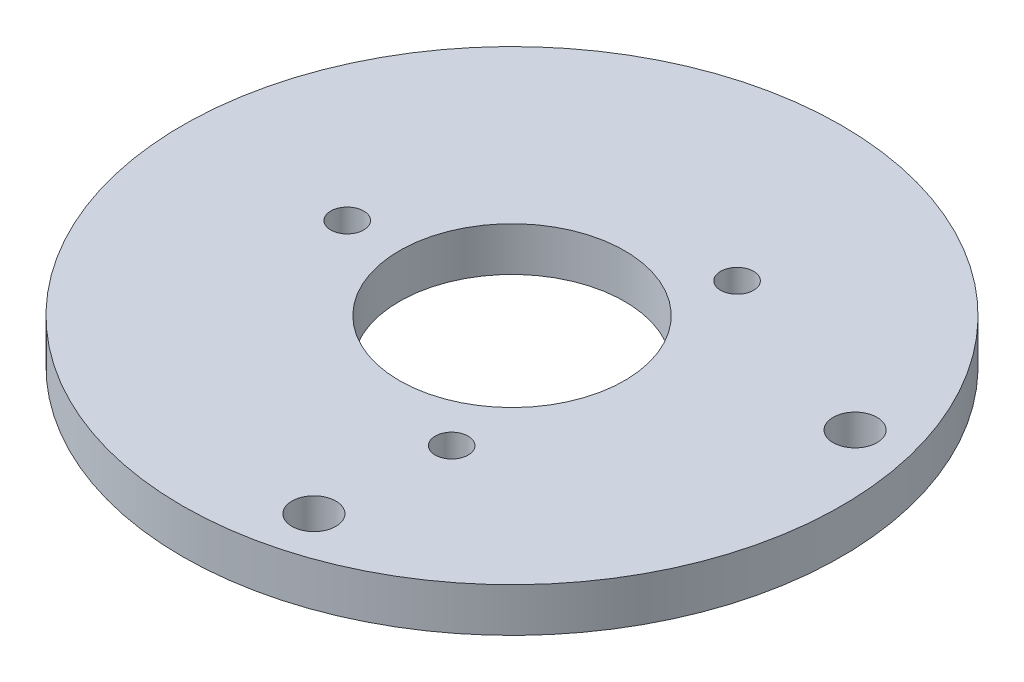
SolidWorks part; units mm, degrees
material "1060 Alloy"
ref_plane "Front Plane" through (0, 0, 0) normal (0, 0, 1) x (1, 0, 0)
ref_plane "Top Plane" through (0, 0, 0) normal (0, 1, 0) x (1, 0, 0)
ref_plane "Right Plane" through (0, 0, 0) normal (1, 0, 0) x (0, 0, -1)
sketch "Sketch1" plane through (0, 0, 0) normal (0, 1, 0) x (1, 0, 0)
  line L0 (-44.2539, 0) -> (44.2539, 0) construction
  arc A0 (-30, 0) -> (30, 0) centre (0, 0) cw
  arc A2 (-30, 0) -> (30, 0) centre (0, 0) ccw
  dimension "D1" = 30
extrude "Boss-Extrude1" add sketch "Sketch1" along normal blind 4
sketch "Sketch2" plane through (0, 4, 0) normal (0, 1, 0) x (1, 0, 0)
  line L2 (0, -44.7868) -> (0, 44.7868) construction
  circle A0 centre (7.5, 12.9904) radius 1.5
  dimension "D1" = 3
  dimension "D2" = 15
  dimension "D3" = 7.5
extrude "Cut-Extrude1" cut sketch "Sketch2" against normal blind 4
pattern_circular "CirPattern1" count 3 over 360 about axis through (0, 0, 0) along (0, 1, 0) of "Cut-Extrude1"
sketch "Sketch3" plane through (0, 4, 0) normal (0, 1, 0) x (1, 0, 0)
  circle A0 centre (0, 0) radius 10.25
extrude "Cut-Extrude2" cut sketch "Sketch3" against normal blind 4
sketch "Sketch4" plane through (0, 4, 0) normal (0, 1, 0) x (1, 0, 0)
  line L2 (0, -44.7868) -> (0, 44.7868) construction
  circle A0 centre (6.5999, -24.6311) radius 2
  dimension "D1" = 4
  dimension "D2" = 6.5999
  dimension "D3" = 25.5
extrude "Cut-Extrude3" cut sketch "Sketch4" against normal blind 4
pattern_circular "CirPattern2" count 2 over 90 about axis through (0, 4, 0) along (0, -1, 0) of "Cut-Extrude3"
